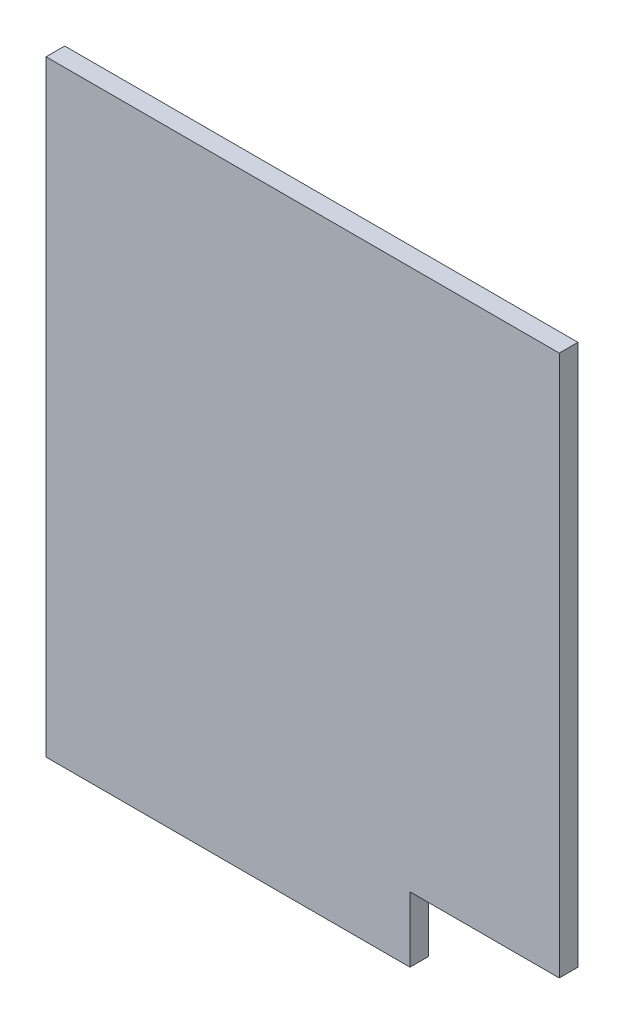
SolidWorks part; units mm, degrees
ref_plane "前视基准面" through (0, 0, 0) normal (0, 0, 1) x (1, 0, 0)
ref_plane "上视基准面" through (0, 0, 0) normal (0, 1, 0) x (1, 0, 0)
ref_plane "右视基准面" through (0, 0, 0) normal (1, 0, 0) x (0, 0, -1)
sketch "草图1" plane through (0, 0, 0) normal (0, 0, 1) x (1, 0, 0)
  line L1 (-27.5, -32.5) -> (27.5, -32.5)
  line L2 (-27.5, -32.5) -> (-27.5, 32.5)
  line L3 (-27.5, 32.5) -> (27.5, 32.5)
  line L4 (27.5, -32.5) -> (27.5, 32.5)
  line L5 (-27.5, -32.5) -> (27.5, 32.5) construction
  line L6 (-27.5, 32.5) -> (27.5, -32.5) construction
  point P0 (0, 0)
  dimension "D1" = 55
  dimension "D2" = 65
extrude "凸台-拉伸1" add sketch "草图1" along normal blind 2
sketch "草图2" plane through (0, 0, 2) normal (0, 0, 1) x (1, 0, 0)
  line L2 (27.5, -32.5) -> (11.5, -32.5)
  line L4 (27.5, -32.5) -> (27.5, -25.5)
  line L5 (27.5, -25.5) -> (11.5, -25.5)
  line L6 (11.5, -32.5) -> (11.5, -25.5)
  dimension "D1" = 16
  dimension "D2" = 7
extrude "切除-拉伸2" cut sketch "草图2" against normal blind 2
